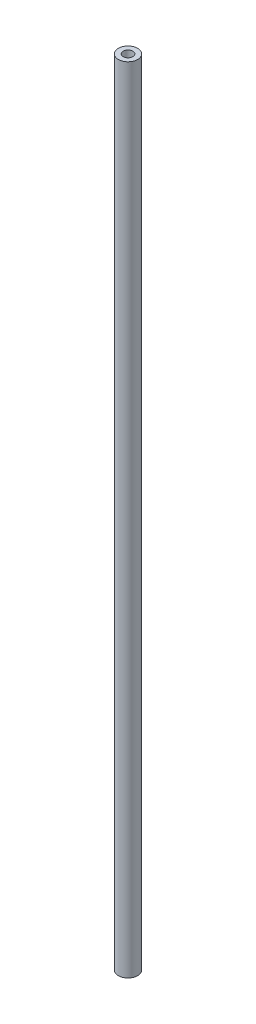
SolidWorks part; units mm, degrees
ref_plane "Alzado" through (0, 0, 0) normal (0, 0, 1) x (1, 0, 0)
ref_plane "Planta" through (0, 0, 0) normal (0, 1, 0) x (1, 0, 0)
ref_plane "Vista lateral" through (0, 0, 0) normal (1, 0, 0) x (0, 0, -1)
sketch "Croquis1" plane through (0, 0, 0) normal (0, 0, 1) x (1, 0, 0)
  line L0 (0, 0) -> (0, 170) construction
  line L1 (-1, 0) -> (-2, 0)
  line L2 (-1, 0) -> (-1, 164)
  line L3 (-1, 164) -> (-2, 164)
  line L4 (-2, 0) -> (-2, 164)
  line L5 (-1, 0) -> (-2, 164) construction
  line L6 (-1, 164) -> (-2, 0) construction
  line L7 (-2, 0) -> (0, 0) construction
  point P4 (-1.5, 82)
  dimension "D1" = 164
  dimension "D2" = 4
  dimension "D3" = 2
revolve "Revolución1" add sketch "Croquis1" angle 360 about L0
